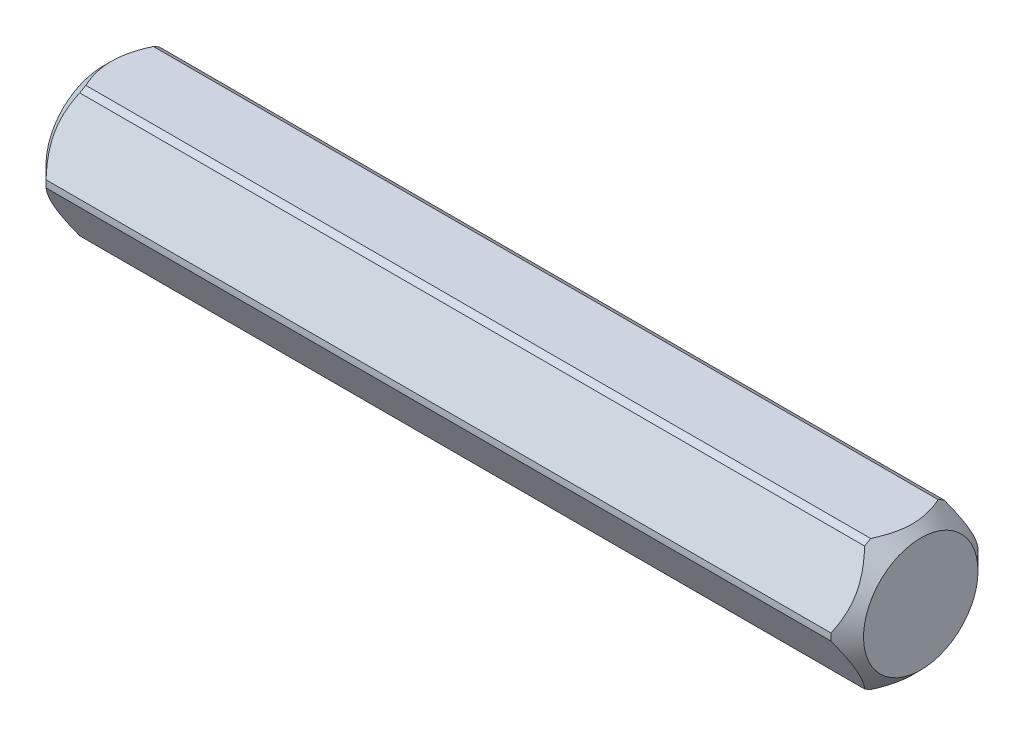
SolidWorks part; units mm, degrees
material "AISI 1045 钢，冷拔"
ref_plane "前视基准面" through (0, 0, 0) normal (0, 0, 1) x (1, 0, 0)
ref_plane "上视基准面" through (0, 0, 0) normal (0, 1, 0) x (1, 0, 0)
ref_plane "右视基准面" through (0, 0, 0) normal (1, 0, 0) x (0, 0, -1)
sketch "草图1" plane through (0, 0, 0) normal (1, 0, 0) x (0, 0, -1)
  line L1 (4.6188, 0) -> (2.3094, 4)
  line L2 (2.3094, 4) -> (-2.3094, 4)
  line L3 (-2.3094, 4) -> (-4.6188, 0)
  line L4 (-4.6188, 0) -> (-2.3094, -4)
  line L5 (-2.3094, -4) -> (2.3094, -4)
  line L6 (2.3094, -4) -> (4.6188, 0)
  circle A1 centre (0, 0) radius 4 construction
  dimension "D1" = 8
extrude "初始整轴" add sketch "草图1" along normal mid plane 50
sketch "草图8" plane through (0, 0, 0) normal (1, 0, 0) x (0, 0, -1)
  circle A0 centre (0, 0) radius 4.5
  circle A1 centre (0, 0) radius 5.5
  dimension "D1" = 9
  dimension "D2" = 1
extrude "整轴外圆" cut sketch "草图8" against normal through all both and the other way through all
sketch "草图10" plane through (0, 0, 0) normal (0, 0, 1) x (1, 0, 0)
  line L0 (25, 0) -> (-25, 0) construction
  line L7 (0, 0) -> (0, 3.7854) construction
  line L8 (-25, 3.7854) -> (25, 3.7854) construction
  line L12 (-25.5, 4.5) -> (-24, 4.5)
  line L13 (-25.5, 4.5) -> (-25.5, 3)
  line L14 (-24, 4.5) -> (-25.5, 3)
  line L15 (-25, 3.7854) -> (-25, 0.2146) construction
  line L16 (25, 4) -> (-25, 4) construction
  line L17 (24, 4.5) -> (25.5, 3)
  line L18 (25.5, 4.5) -> (25.5, 3)
  line L19 (25.5, 4.5) -> (24, 4.5)
  line L20 (-25, 0.2146) -> (-25, -0.2146) construction
  point P6 (0, 0)
  point P8 (0, 0)
  dimension "D1" = 1.5
  dimension "D2" = 1.5
  dimension "D3" = 0.5
  dimension "D4" = 0.5
revolve "初始倒角" cut sketch "草图10" angle 360 about L0
sketch "草图2" [suppressed] plane through (25, 0, 0) normal (1, 0, 0) x (0, 0, -1)
  circle A0 centre (0, 0) radius 3.5
  circle A1 centre (0, 0) radius 4.5
  dimension "D1" = 9
  dimension "右侧凸台直径" = 7
extrude "右侧凸台切除" [suppressed] cut sketch "草图2" against normal blind 5
chamfer "右侧凸台倒角" [suppressed] distance 0.3 angle 45
sketch "草图3" [suppressed] plane through (-25, 0, 0) normal (-1, 0, 0) x (0, 0, 1)
  circle A0 centre (0, 0) radius 3.5
  circle A1 centre (0, 0) radius 4.5
  dimension "D1" = 9
  dimension "左侧凸台直径" = 7
extrude "左侧凸台切除" [suppressed] cut sketch "草图3" against normal blind 5
chamfer "左侧凸台倒角" [suppressed] distance 0.3 angle 45
sketch "草图4" plane through (0, 0, 0) normal (0, 0, 1) x (1, 0, 0)
  line L0 (-13.3489, 0) -> (13.3489, 0) construction
  line L3 (14.5, 4.5) -> (15.5, 4.5)
  line L4 (14.5, 4.5) -> (14.5, 3.7)
  line L5 (14.5, 3.7) -> (15.5, 3.7)
  line L6 (15.5, 4.5) -> (15.5, 3.7)
  line L7 (15, 4.5) -> (15, -2.1923) construction
  point P6 (0, 0)
  dimension "D1" = 3.7
  dimension "D2" = 4.5
  dimension "槽1宽度" = 1
  dimension "槽1中心距离" = 15
revolve "卡簧槽1" [suppressed] cut sketch "草图4" angle 360 about L0
sketch "草图5" plane through (0, 0, 0) normal (0, 0, 1) x (1, 0, 0)
  line L0 (-10.9541, 0) -> (10.9541, 0) construction
  line L3 (-15.5, 4.5) -> (-14.5, 4.5)
  line L4 (-15.5, 4.5) -> (-15.5, 3.7)
  line L5 (-15.5, 3.7) -> (-14.5, 3.7)
  line L6 (-14.5, 4.5) -> (-14.5, 3.7)
  line L7 (-15, 4.5) -> (-15, -2.3192) construction
  point P6 (0, 0)
  dimension "D1" = 3.7
  dimension "D2" = 4.5
  dimension "槽2宽度" = 1
  dimension "槽2中心距离" = 15
revolve "卡簧槽2" [suppressed] cut sketch "草图5" angle 360 about L0
sketch "草图6" [suppressed] plane through (25, 0, 0) normal (1, 0, 0) x (0, 0, -1)
  circle A0 centre (0, 0) radius 2.5
  dimension "右侧攻丝直径" = 5
extrude "右侧攻丝切除" [suppressed] cut sketch "草图6" against normal blind 5
chamfer "右侧攻丝倒角" [suppressed] distance 0.5 angle 45
sketch "草图7" [suppressed] plane through (-25, 0, 0) normal (-1, 0, 0) x (0, 0, 1)
  circle A0 centre (0, 0) radius 2.5
  dimension "左侧攻丝直径" = 5
extrude "左侧攻丝切除" [suppressed] cut sketch "草图7" against normal blind 5
chamfer "左侧攻丝倒角" [suppressed] distance 0.5 angle 45
other "冻结***"
